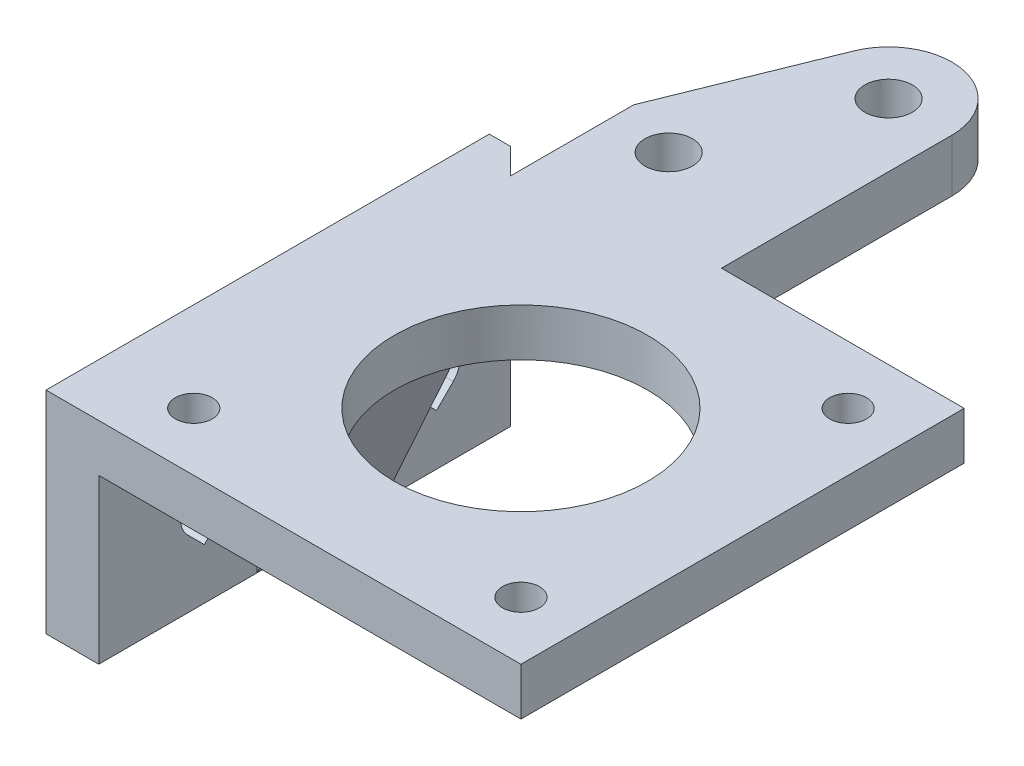
SolidWorks part; units mm, degrees
material "Printed PLA"
ref_plane "Front Plane" through (0, 0, 0) normal (0, 0, 1) x (1, 0, 0)
ref_plane "Top Plane" through (0, 0, 0) normal (0, 1, 0) x (1, 0, 0)
ref_plane "Right Plane" through (0, 0, 0) normal (1, 0, 0) x (0, 0, -1)
sketch "Sketch1" plane through (0, 0, 0) normal (0, 0, 1) x (1, 0, 0)
  line L0 (0, 0) -> (45, 0)
  line L1 (45, 0) -> (45, -4.5)
  line L2 (45, -4.5) -> (5, -4.5)
  line L3 (5, -4.5) -> (5, -20)
  line L4 (5, -20) -> (0, -20)
  line L5 (0, -20) -> (0, 0)
  dimension "D1" = 4.5
  dimension "D2" = 45
  dimension "D3" = 5
  dimension "D4" = 20
extrude "Boss-Extrude1" add sketch "Sketch1" along normal mid plane 42
sketch "Sketch2" plane through (0, 0, 0) normal (0, 1, 0) x (1, 0, 0)
  line L1 (24, 0) -> (45, 0) construction
  line L2 (45, -21) -> (45, 21) construction
  line L3 (45, 0) -> (45.4311, 0) construction
  line L4 (39.5, -15.5) -> (8.5, -15.5) construction
  line L5 (8.5, -15.5) -> (8.5, 15.5) construction
  line L6 (8.5, 15.5) -> (39.5, 15.5) construction
  line L7 (39.5, 15.5) -> (39.5, -15.5) construction
  line L8 (39.5, -15.5) -> (8.5, 15.5) construction
  circle A0 centre (24, 0) radius 12
  circle A1 centre (39.5, 15.5) radius 1.75
  circle A2 centre (8.5, 15.5) radius 1.75 construction
  circle A3 centre (8.5, -15.5) radius 1.75
  circle A4 centre (39.5, -15.5) radius 1.75
  dimension "D1" = 24
  dimension "D4" = 3.5
  dimension "D2" = 21
  dimension "D3" = 31
extrude "Cut-Extrude1" cut sketch "Sketch2" against normal up to next
sketch "Sketch3" plane through (0, 0, 0) normal (0, 0, 1) x (1, 0, 0)
  line L0 (5, -20) -> (12, -4.5)
  line L1 (5, -4.5) -> (45, -4.5) construction
  line L2 (12, -4.5) -> (5, -4.5)
  line L3 (5, -4.5) -> (5, -20)
  dimension "D1" = 7
extrude "Boss-Extrude2" add sketch "Sketch3" along normal mid plane 12
sketch "Sketch4" plane through (5, 0, 0) normal (1, 0, 0) x (0, 0, -1)
  line L0 (9.409, -13.591) -> (11, -15.182)
  line L1 (11, -15.182) -> (12.591, -13.591)
  line L2 (-12.591, -13.591) -> (-11, -15.182)
  line L3 (-11, -15.182) -> (-9.409, -13.591)
  line L4 (-11, -15.182) -> (-11, -12) construction
  line L5 (11, -12) -> (11, -15.182) construction
  line L6 (11, -12) -> (-11, -12) construction
  line L7 (0, -12) -> (0, 0) construction
  arc A0 (-9.409, -13.591) -> (-12.591, -13.591) centre (-11, -12) ccw
  arc A1 (12.591, -13.591) -> (9.409, -13.591) centre (11, -12) ccw
  dimension "D1" = 4.5
  dimension "D2" = 22
  dimension "D3" = 12
extrude "Cut-Extrude2" cut sketch "Sketch4" against normal through all
sketch "Sketch5" plane through (0, 0, 0) normal (0, 1, 0) x (1, 0, 0)
  line L0 (4, 21) -> (4, 28) construction
  line L1 (45, 21) -> (0, 21) construction
  line L2 (4.4379, 30.25) -> (10.4379, 45.0824)
  line L3 (22, 42.8324) -> (22, 21)
  line L4 (22, 21) -> (4.4379, 21)
  line L5 (0, -21) -> (0, 21) construction
  line L6 (4.4379, 21) -> (4.4379, 30.25)
  line L7 (4, 21) -> (4.4379, 21) construction
  arc A0 (4, 28) -> (4.4379, 30.25) centre (10, 28) cw construction
  arc A1 (10.4379, 45.0824) -> (22, 42.8324) centre (16, 42.8324) cw
  circle A2 centre (10, 28) radius 2.25
  circle A3 centre (16, 42.8324) radius 2.25
  dimension "D1" = 4.5
  dimension "D3" = 10
  dimension "D6" = 6
  dimension "D2" = 7
  dimension "D4" = 16
  dimension "D5" = 6
extrude "Boss-Extrude3" add sketch "Sketch5" against normal up to surface (4.5 mm away) up to face at (37.75, -4.5, -15.5)
chamfer "Chamfer1" distance 3 angle 45 1 edges
sketch "Sketch6" plane through (0, -4.5, 0) normal (0, -1, 0) x (1, 0, 0)
  line L0 (5, -18) -> (22, -21)
  line L1 (22, -21) -> (22, -42.8324)
  line L2 (10.4379, -45.0824) -> (4.4379, -30.25)
  line L6 (4.4379, -18.5621) -> (5, -18)
  line L7 (4.4379, -18.5621) -> (4.4379, -30.25)
  arc A0 (22, -42.8324) -> (10.4379, -45.0824) centre (16, -42.8324) cw
  circle A2 centre (10, -28) radius 2.25
  circle A3 centre (16, -42.8324) radius 2.25
  circle A4 centre (16, -42.8324) radius 2.25 construction
extrude "Boss-Extrude4" add sketch "Sketch6" along normal blind 0.5
